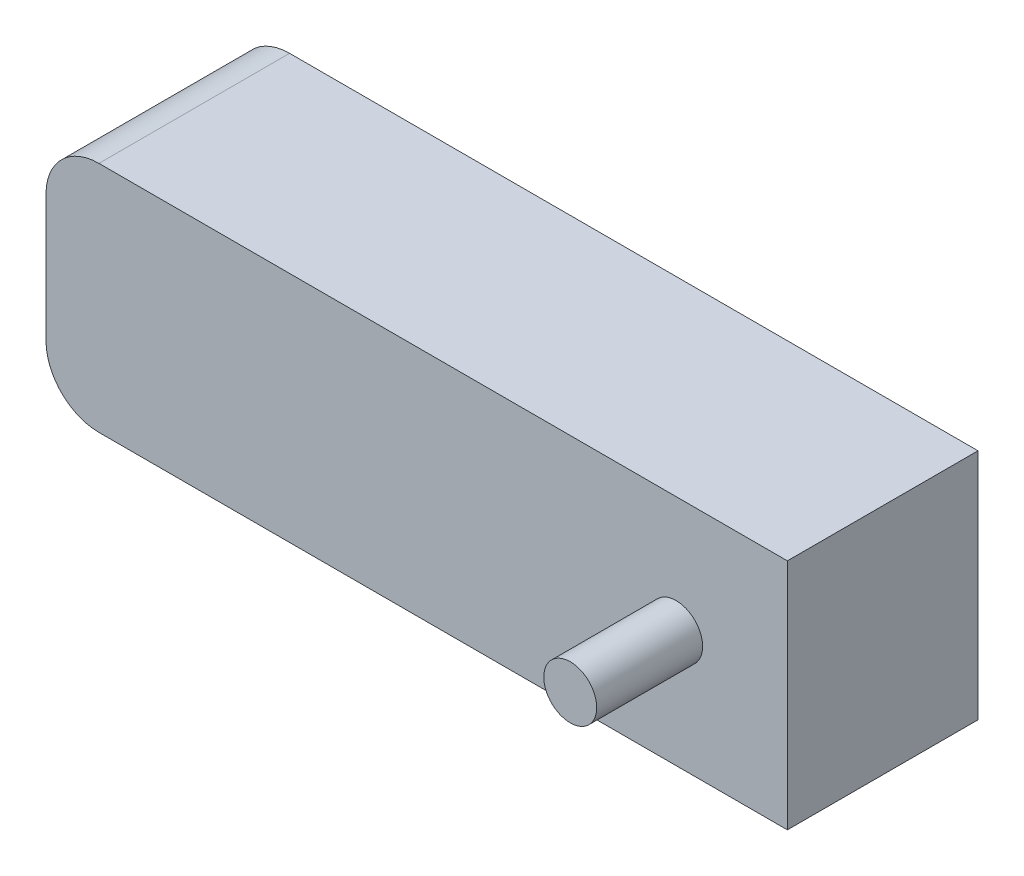
SolidWorks part; units mm, degrees
ref_plane "Alzado" through (0, 0, 0) normal (0, 0, 1) x (1, 0, 0)
ref_plane "Planta" through (0, 0, 0) normal (0, 1, 0) x (1, 0, 0)
ref_plane "Vista lateral" through (0, 0, 0) normal (1, 0, 0) x (0, 0, -1)
sketch "Croquis1" plane through (0, 0, 0) normal (0, 0, 1) x (1, 0, 0)
  line L1 (0, 0) -> (70, 0)
  line L2 (0, 0) -> (0, 22)
  line L3 (0, 22) -> (70, 22)
  line L4 (70, 0) -> (70, 22)
extrude "Saliente-Extruir1" add sketch "Croquis1" along normal blind 18
sketch "Croquis2" plane through (0, 0, 18) normal (0, 0, 1) x (1, 0, 0)
  line L0 (62, 22) -> (62, 0) construction
  line L1 (70, 22) -> (0, 22) construction
  line L2 (0, 0) -> (70, 0) construction
  line L3 (70, 0) -> (70, 22) construction
  line L6 (57, 22) -> (57, 0) construction
  line L7 (62, 11) -> (57, 11) construction
  circle A0 centre (59.5, 11) radius 2.5
  dimension "D1" = 8
  dimension "D2" = 5
extrude "Saliente-Extruir2" add sketch "Croquis2" along normal blind 10
fillet "Redondeo3" radius 5 1 edges at (0, 22, 9)
fillet "Redondeo4" radius 5 1 edges at (0, 0, 9)
sketch "Croquis3" plane through (0, 0, 28) normal (0, 0, 1) x (1, 0, 0)
  circle A1 centre (59.5, 11) radius 2.5
  dimension "D1" = 5
